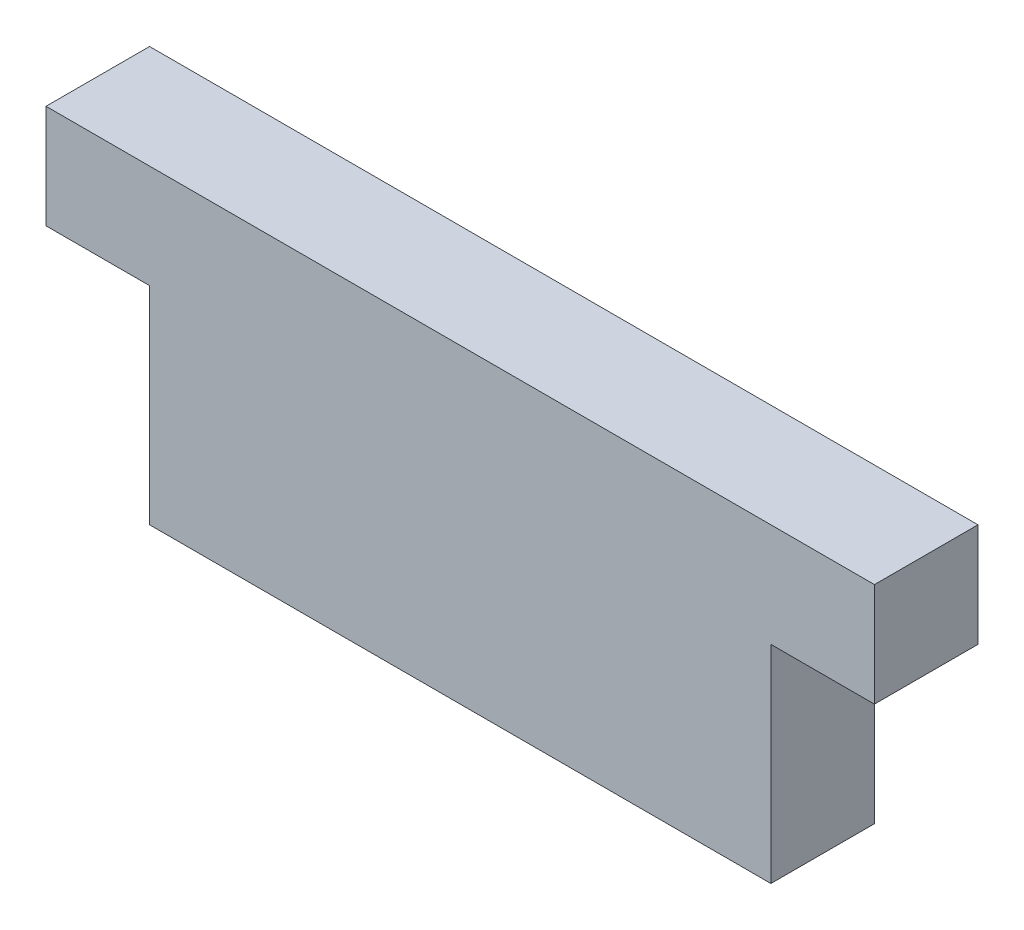
SolidWorks part; units mm, degrees
ref_plane "Front Plane" through (0, 0, 0) normal (0, 0, 1) x (1, 0, 0)
ref_plane "Top Plane" through (0, 0, 0) normal (0, 1, 0) x (1, 0, 0)
ref_plane "Right Plane" through (0, 0, 0) normal (1, 0, 0) x (0, 0, -1)
sketch "Sketch1" plane through (0, 0, 0) normal (0, 0, 1) x (1, 0, 0)
  line L1 (0, 0) -> (-30, 0)
  line L2 (0, 0) -> (0, -10)
  line L3 (0, -10) -> (-30, -10)
  line L4 (-30, 0) -> (-30, -10)
  line L5 (-35, 0) -> (5, 0)
  line L6 (-35, 0) -> (-35, 5)
  line L7 (-35, 5) -> (5, 5)
  line L8 (5, 0) -> (5, 5)
  dimension "D1" = 10
  dimension "D2" = 30
  dimension "D3" = 40
  dimension "D4" = 5
  dimension "D5" = 5
extrude "Boss-Extrude1" add sketch "Sketch1" along normal blind 5 contours L1 L4 L3 L2 | L5 L8 L7 L6 L1
